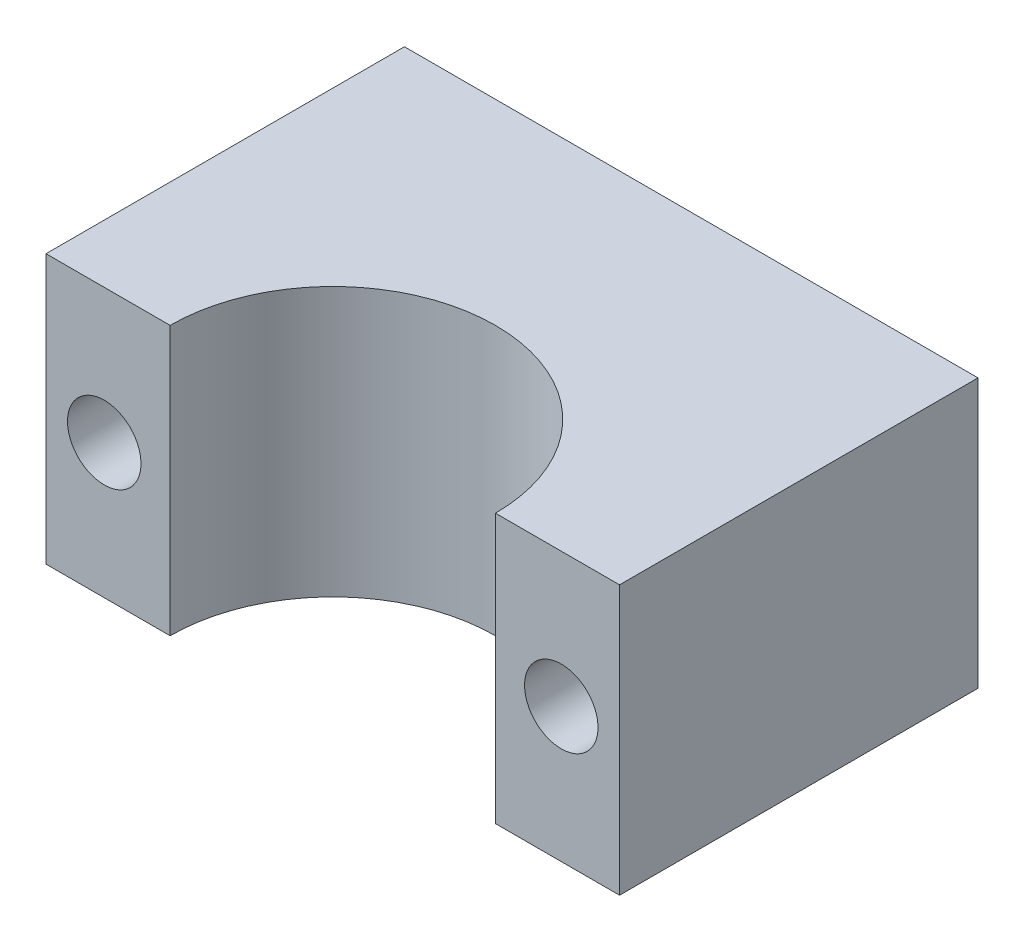
SolidWorks part; units mm, degrees
material "6061 Alloy"
ref_plane "Front Plane" through (0, 0, 0) normal (0, 0, 1) x (1, 0, 0)
ref_plane "Top Plane" through (0, 0, 0) normal (0, 1, 0) x (1, 0, 0)
ref_plane "Right Plane" through (0, 0, 0) normal (1, 0, 0) x (0, 0, -1)
sketch "Sketch2" plane through (0, 0, 0) normal (0, 1, 0) x (1, 0, 0)
  line L0 (0, 0) -> (53395.907, 0) construction
  line L1 (-16, 20) -> (16, 20)
  line L2 (-16, 20) -> (-16, 0)
  line L4 (16, 20) -> (16, 0)
  line L5 (-16, 20) -> (0, 0) construction
  line L6 (0, 0) -> (16, 20) construction
  line L7 (-16, 0) -> (-9.075, 0)
  line L8 (9.075, 0) -> (16, 0)
  arc A0 (9.075, 0) -> (-9.075, 0) centre (0, 0) ccw
  dimension "D1" = 18.15
  dimension "D2" = 32
  dimension "D3" = 16
  dimension "D4" = 20
extrude "Boss-Extrude1" add sketch "Sketch2" along normal blind 15
sketch "Sketch3" plane through (0, 0, -20) normal (0, 0, -1) x (-1, 0, 0)
  line L4 (-12.75, 7.5) -> (12.75, 7.5) construction
  line L5 (-16, 15) -> (16, 15) construction
  line L6 (-16, 0) -> (16, 0) construction
  line L7 (0, 7.5) -> (0, 13.7198) construction
  line L8 (-16, 15) -> (-16, 0) construction
  line L9 (16, 15) -> (16, 0) construction
  circle A0 centre (-12.75, 7.5) radius 2.05
  circle A1 centre (12.75, 7.5) radius 2.05
  dimension "D1" = 4.1
  dimension "D2" = 25.5
extrude "Cut-Extrude1" cut sketch "Sketch3" against normal through all both and the other way through all
